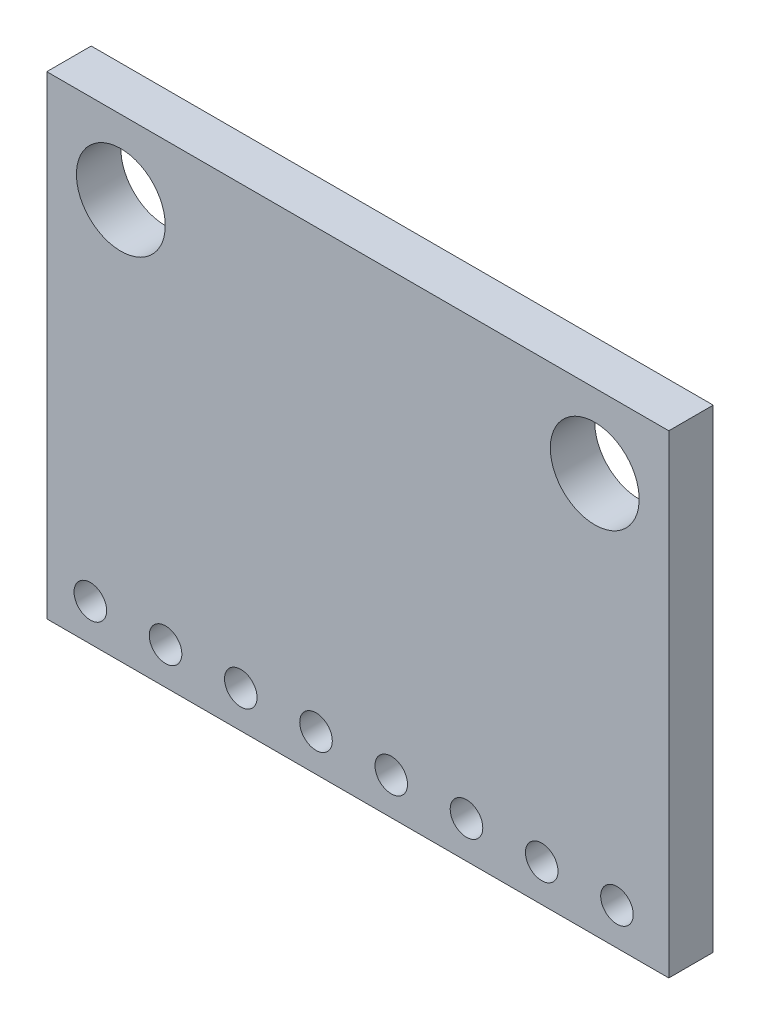
SolidWorks part; units mm, degrees
ref_plane "Alzado" through (0, 0, 0) normal (0, 0, 1) x (1, 0, 0)
ref_plane "Planta" through (0, 0, 0) normal (0, 1, 0) x (1, 0, 0)
ref_plane "Vista lateral" through (0, 0, 0) normal (1, 0, 0) x (0, 0, -1)
sketch "Croquis1" plane through (0, 0, 0) normal (0, 0, 1) x (1, 0, 0)
  line L0 (0, 0) -> (0, 8) construction
  line L1 (10.5, -8) -> (-10.5, -8)
  line L2 (10.5, -8) -> (10.5, 8)
  line L3 (10.5, 8) -> (-10.5, 8)
  line L4 (-10.5, -8) -> (-10.5, 8)
  line L5 (10.5, -8) -> (-10.5, 8) construction
  line L6 (10.5, 8) -> (-10.5, -8) construction
  circle A0 centre (-8, 5.5) radius 1.5
  circle A1 centre (8, 5.5) radius 1.5
  point P0 (0, 0)
  dimension "D3" = 3
  dimension "D1" = 16
  dimension "D2" = 21
  dimension "D4" = 2.5
  dimension "D5" = 2.5
extrude "Saliente-Extruir1" add sketch "Croquis1" along normal blind 1.5
sketch "Croquis2" plane through (0, 0, 0) normal (0, 0, -1) x (-1, 0, 0)
  circle A0 centre (-8.75, -6.75) radius 0.55
  circle A1 centre (-6.21, -6.75) radius 0.55
  circle A2 centre (-3.67, -6.75) radius 0.55
  circle A3 centre (-1.13, -6.75) radius 0.55
  circle A4 centre (1.41, -6.75) radius 0.55
  circle A5 centre (3.95, -6.75) radius 0.55
  circle A6 centre (6.49, -6.75) radius 0.55
  circle A7 centre (9.03, -6.75) radius 0.55
  dimension "D1" = 1.1
  dimension "D2" = 8
extrude "Cortar-Extruir1" cut sketch "Croquis2" against normal up to surface (1.5 mm away) up to face at (-6.5, 5.5, 1.5)
